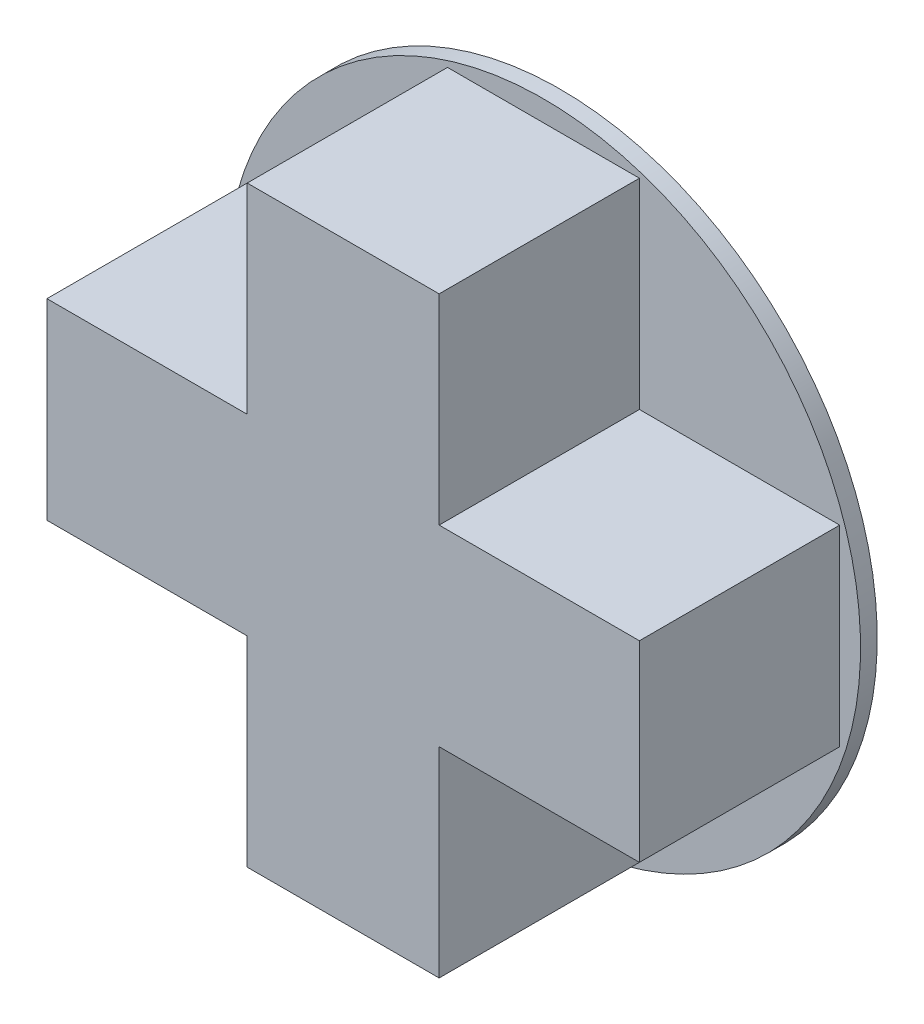
SolidWorks part; units mm, degrees
ref_plane "Front Plane" through (0, 0, 0) normal (0, 0, 1) x (1, 0, 0)
ref_plane "Top Plane" through (0, 0, 0) normal (0, 1, 0) x (1, 0, 0)
ref_plane "Right Plane" through (0, 0, 0) normal (1, 0, 0) x (0, 0, -1)
sketch "Sketch1" plane through (0, 0, 0) normal (0, 0, 1) x (1, 0, 0)
  line L0 (-2.875, 2.875) -> (-2.875, 8.875)
  line L1 (-2.875, -8.875) -> (2.875, -8.875)
  line L2 (-2.875, -8.875) -> (-2.875, -2.875)
  line L3 (-2.875, 8.875) -> (2.875, 8.875)
  line L4 (2.875, -8.875) -> (2.875, -2.875)
  line L5 (-2.875, 2.875) -> (2.875, -2.875) construction
  line L6 (2.875, 2.875) -> (-2.875, -2.875) construction
  line L7 (-8.875, -2.875) -> (-2.875, -2.875)
  line L8 (-8.875, -2.875) -> (-8.875, 2.875)
  line L9 (-8.875, 2.875) -> (-2.875, 2.875)
  line L10 (8.875, -2.875) -> (8.875, 2.875)
  line L18 (2.875, 2.875) -> (2.875, 8.875)
  line L19 (2.875, 2.875) -> (8.875, 2.875)
  line L20 (2.875, -2.875) -> (8.875, -2.875)
  point P0 (0, 0)
  point P6 (0, 0)
  dimension "D1" = 17.75
  dimension "D2" = 17.75
  dimension "D3" = 5.75
  dimension "D4" = 5.75
  dimension "D5" = 6
  dimension "D6" = 6
  dimension "D7" = 5.75
  dimension "D8" = 6
  dimension "D9" = 6
  dimension "D10" = 8.875
  dimension "D11" = 8.875
extrude "Boss-Extrude1" add sketch "Sketch1" along normal blind 6
sketch "Sketch2" plane through (0, 0, 0) normal (0, 0, -1) x (-1, 0, 0)
  circle A0 centre (0, 0) radius 9.5
  dimension "D1" = 19
extrude "Boss-Extrude2" add sketch "Sketch2" along normal blind 0.5
sketch "Sketch4" plane through (0, 0, -0.5) normal (0, 0, -1) x (-1, 0, 0)
  line L0 (-9.5, 0) -> (9.5, 0) construction
  line L1 (0, 9.5) -> (0, -9.5) construction
  circle A0 centre (0, 0) radius 9.5 construction
  circle A1 centre (6, 0) radius 1.75
  circle A2 centre (0, -6) radius 1.75
  circle A3 centre (-6, 0) radius 1.75
  circle A4 centre (0, 6) radius 1.75
  point P18 (0, 0)
  point P19 (0, 0)
  dimension "D1" = 3.5
  dimension "D4" = 3.5
  dimension "D2" = 3.5
  dimension "D5" = 3.5
  dimension "D3" = 4
extrude "Cut-Extrude2" cut sketch "Sketch4" against normal blind 0.75
